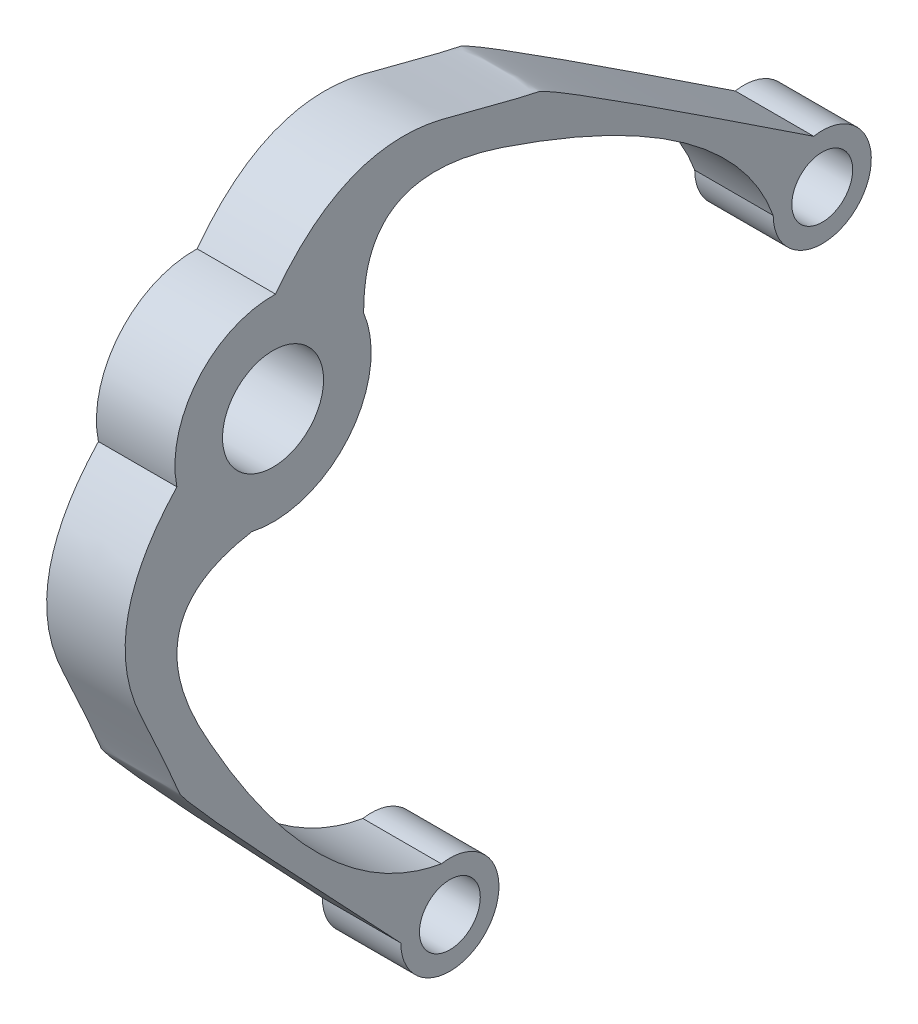
SolidWorks part; units mm, degrees
ref_plane "前视基准面" through (0, 0, 0) normal (0, 0, 1) x (1, 0, 0)
ref_plane "上视基准面" through (0, 0, 0) normal (0, 1, 0) x (1, 0, 0)
ref_plane "右视基准面" through (0, 0, 0) normal (1, 0, 0) x (0, 0, -1)
sketch "草图1" plane through (0, 0, 0) normal (1, 0, 0) x (0, 0, -1)
  circle A0 centre (0, 0) radius 2.575
  circle A1 centre (0, 0) radius 5
  dimension "D1" = 10
  dimension "D2" = 5.15
extrude "凸台-拉伸1" add sketch "草图1" along normal blind 4
sketch "草图2" plane through (0, 0, 0) normal (-1, 0, 0) x (0, 0, 1)
  line L0 (20.8649, 1.5798) -> (7.8412, -9.3464) construction
  line L1 (20.8649, 1.5798) -> (7.8412, -9.3464) construction
  line L2 (0, 0) -> (-6.1273, -5.1405) construction
  line L3 (-0.1279, 4.9984) -> (-4.6492, 1.8397)
  line L4 (4.9, -0.9948) -> (1.0036, -4.8982)
  line L5 (-20.6903, 1.224) -> (-17.3086, 4.0611) construction
  line L6 (-21.505, -8.9602) -> (-29.4741, 0.5387) construction
  circle A0 centre (0, 0) radius 5 construction
  arc A1 (-4.6193, 1.9137) -> (-4.6492, 1.8397) centre (0, 0) ccw
  arc A2 (-27.555, -1.7488) -> (-25.4896, -4.2107) centre (-27.9896, -4.2107) ccw
  arc A3 (-7.8412, 9.3464) -> (7.8412, -9.3464) centre (0, 0) ccw construction
  circle A4 centre (-27.9896, -4.2107) radius 1.55
  circle A5 centre (-9.0118, -26.8316) radius 1.55
  arc A6 (-6.5118, -26.8316) -> (-8.5772, -24.3696) centre (-9.0118, -26.8316) cw
  arc A7 (1.0036, -4.8982) -> (1.0817, -4.8816) centre (0, 0) ccw
  spline S0 degree 2 poles (-0.1279, 4.9984) (-3.7195, 9.775) (-12.7298, 7.375) (-14.2105, 7.1045) (-27.555, -1.7488) knots 0 0 0 0.416313 0.733126 1 1 1
  spline S1 degree 2 poles (-4.6193, 1.9137) (-4.5625, 8.1124) (-23.3559, 1.7331) (-25.4896, -4.2107) knots 0 0 0 0.386206 1 1 1
  spline S2 degree 2 poles (1.0817, -4.8816) (7.1959, -5.9031) (-2.353, -23.3016) (-8.5772, -24.3696) knots 0 0 0 0.386206 1 1 1
  spline S3 degree 2 poles (4.9, -0.9948) (8.9797, -5.3619) (5.05, -13.818) (4.5263, -15.2291) (-6.5118, -26.8316) knots 0 0 0 0.416313 0.733126 1 1 1
  dimension "D3" = 5
extrude "凸台-拉伸2" add sketch "草图2" against normal blind 4
